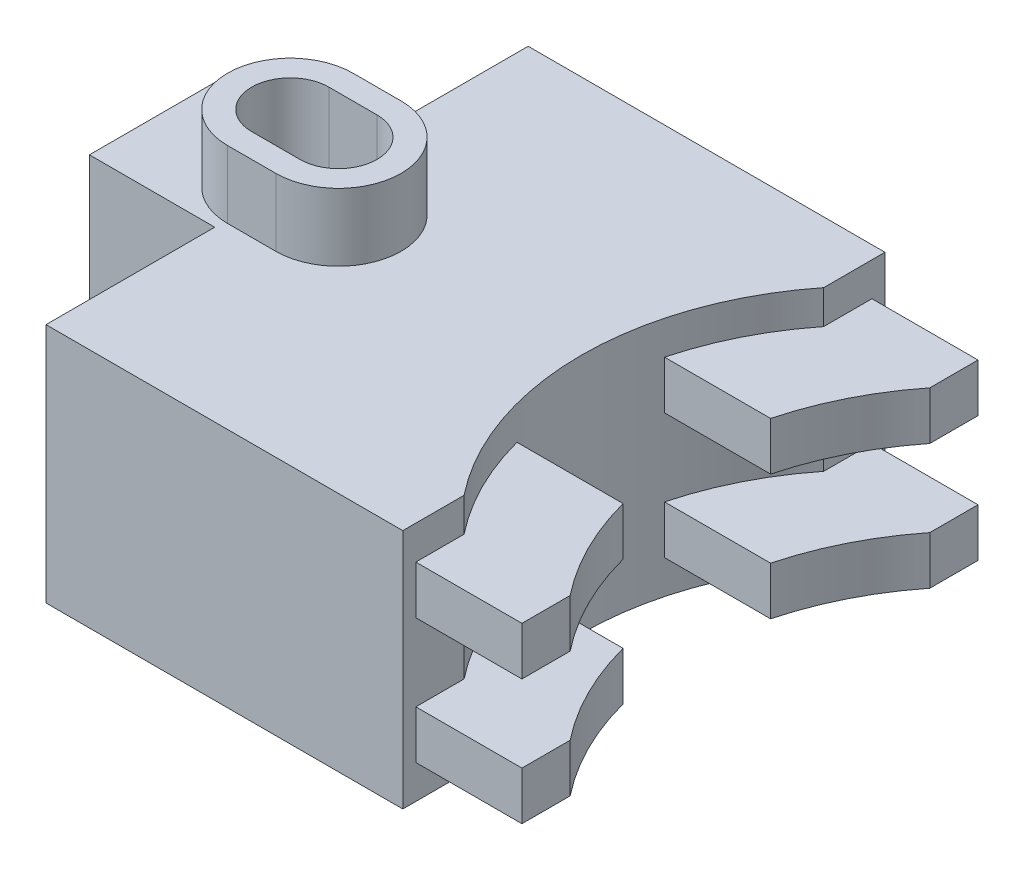
SolidWorks part; units mm, degrees
ref_plane "前视基准面" through (0, 0, 0) normal (0, 0, 1) x (1, 0, 0)
ref_plane "上视基准面" through (0, 0, 0) normal (0, 1, 0) x (1, 0, 0)
ref_plane "右视基准面" through (0, 0, 0) normal (1, 0, 0) x (0, 0, -1)
sketch "草图1" plane through (0, 0, 0) normal (0, 1, 0) x (1, 0, 0)
  line L0 (18.5, 25) -> (18.5, 18.6481)
  line L1 (-18.5, 25) -> (18.5, 25)
  line L2 (-18.5, 25) -> (-18.5, 7.5)
  line L3 (-18.5, -25) -> (18.5, -25)
  line L5 (-18.5, 25) -> (18.5, -25) construction
  line L6 (-18.5, -25) -> (18.5, 25) construction
  line L7 (-18.5, -7.5) -> (-31.5, -7.5)
  line L10 (-18.5, 7.5) -> (-31.5, 7.5)
  line L11 (-31.5, -7.5) -> (-31.5, 7.5)
  line L12 (0, 0) -> (-31.5, 7.5) construction
  line L13 (0, 0) -> (-31.5, -7.5) construction
  line L14 (-18.5, -7.5) -> (-18.5, -25)
  line L15 (18.5, -18.6481) -> (18.5, -25)
  circle A0 centre (42, 0) radius 30
  point P0 (0, 0)
  point P10 (0, 0)
  dimension "D3" = 60
  dimension "D1" = 50
  dimension "D2" = 37
  dimension "D4" = 42
  dimension "D5" = 15
  dimension "D6" = 13
extrude "凸台-拉伸1" add sketch "草图1" along normal mid plane 25
ref_plane "基准面1" through (0, 4, 0) normal (0, 1, 0) x (1, 0, 0)
sketch "草图2" plane through (0, 4, 0) normal (0, 1, 0) x (1, 0, 0)
  line L0 (18.5, 23.6481) -> (29.5, 23.6481)
  line L1 (0, 0) -> (58.4731, 0) construction
  line L2 (12.9913, 7.6481) -> (23.9913, 7.6481)
  line L3 (18.5, 25) -> (18.5, 18.6481) construction
  line L4 (29.5, 23.6481) -> (29.5, 18.6481)
  line L5 (12.9913, -7.6481) -> (23.9913, -7.6481)
  line L6 (18.5, -23.6481) -> (29.5, -23.6481)
  line L7 (29.5, -23.6481) -> (29.5, -18.6481)
  line L8 (18.5, 23.6481) -> (18.5, 18.6481)
  line L9 (18.5, -18.6481) -> (18.5, -23.6481)
  arc A2 (18.5, 18.6481) -> (12.9913, 7.6481) centre (42, 0) ccw
  arc A3 (29.5, 18.6481) -> (23.9913, 7.6481) centre (53, 0) ccw
  arc A4 (23.9913, -7.6481) -> (29.5, -18.6481) centre (53, 0) ccw
  arc A5 (12.9913, -7.6481) -> (18.5, -18.6481) centre (42, 0) ccw
  dimension "D1" = 11
  dimension "D2" = 11
  dimension "D4" = 60
  dimension "D3" = 5
  dimension "D5" = 16
extrude "凸台-拉伸3" add sketch "草图2" along normal blind 5 contours A3 L4 L0 L8 A2 L2 | A4 L5 A2 L9 L6 L7
mirror "镜向1" about plane through (0, 0, 0) normal (0, 1, 0) of "凸台-拉伸3"
sketch "草图3" plane through (0, 12.5, 0) normal (0, 1, 0) x (1, 0, 0)
  line L0 (-18.1708, 6.5) -> (-13.1708, 6.5)
  line L1 (-13.1708, -6.5) -> (-25.9735, -6.5)
  arc A0 (-18.1708, 6.5) -> (-18.1708, -6.5) centre (-18.1708, 0) ccw
  arc A1 (-13.1708, -6.5) -> (-13.1708, 6.5) centre (-13.1708, 0) ccw
  dimension "D1" = 13
  dimension "D2" = 13
  dimension "D3" = 5
extrude "凸台-拉伸4" add sketch "草图3" along normal blind 7 contours L1 A1 L0 A0
sketch "草图5" plane through (0, 19.5, 0) normal (0, 1, 0) x (1, 0, 0)
  line L0 (-18.1708, 6.5) -> (-13.1708, 6.5)
  line L1 (-13.1708, -6.5) -> (-18.1708, -6.5)
  arc A0 (-13.1708, -6.5) -> (-13.1708, 6.5) centre (-13.1708, 0) ccw
  arc A1 (-18.1708, 6.5) -> (-18.1708, -6.5) centre (-18.1708, 0) ccw
extrude "凸台-拉伸5" add sketch "草图5" against normal blind 45
sketch "草图6" plane through (0, 19.5, 0) normal (0, 1, 0) x (1, 0, 0)
  line L0 (-18.1708, 4) -> (-13.1708, 4)
  line L1 (-13.1708, -4) -> (-18.1708, -4)
  arc A0 (-18.1708, 4) -> (-18.1708, -4) centre (-18.1708, 0) ccw
  arc A1 (-13.1708, -4) -> (-13.1708, 4) centre (-13.1708, 0) ccw
extrude "切除-拉伸1" cut sketch "草图6" against normal blind 45
